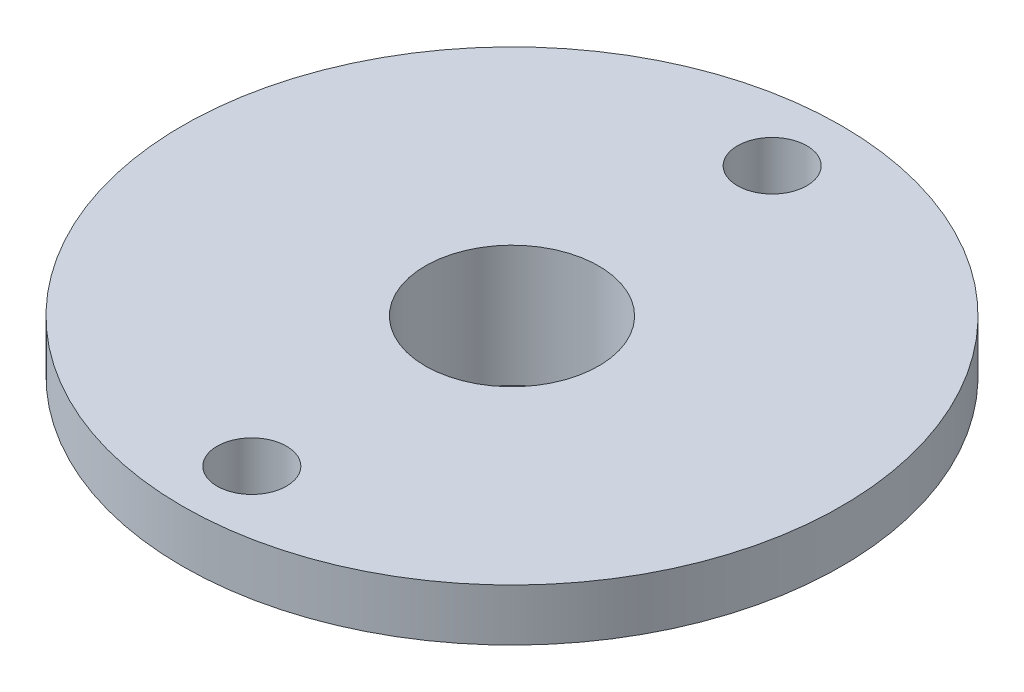
SolidWorks part; units mm, degrees
ref_plane "Plan de face" through (0, 0, 0) normal (0, 0, 1) x (1, 0, 0)
ref_plane "Plan de dessus" through (0, 0, 0) normal (0, 1, 0) x (1, 0, 0)
ref_plane "Plan de droite" through (0, 0, 0) normal (1, 0, 0) x (0, 0, -1)
sketch "Esquisse1" plane through (0, 0, 0) normal (0, 1, 0) x (1, 0, 0)
  circle A0 centre (0, 0) radius 5
extrude "Extrusion1" add sketch "Esquisse1" along normal blind 2
sketch "Esquisse2" plane through (0, 2, 0) normal (0, 1, 0) x (-1, 0, 0)
  circle A0 centre (0, 0) radius 9.5
extrude "Extrusion2" add sketch "Esquisse2" along normal blind 1.5
sketch "Esquisse3" plane through (0, 3.5, 0) normal (0, 1, 0) x (-1, 0, 0)
  circle A0 centre (0, 0) radius 7.5 construction
  circle A1 centre (0, 0) radius 2.5
  circle A2 centre (0, -7.5) radius 1
  circle A3 centre (0, 7.5) radius 1
extrude "Extrusion3" cut sketch "Esquisse3" against normal through all
